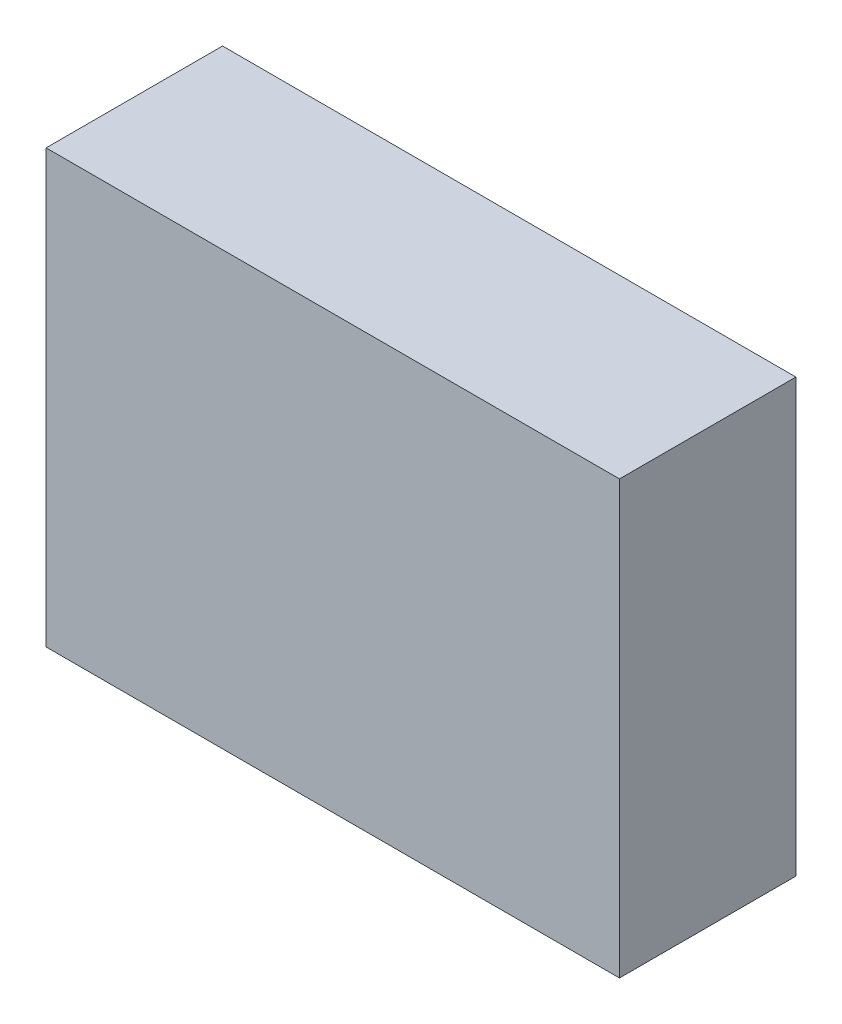
SolidWorks part; units mm, degrees
ref_plane "前视基准面" through (0, 0, 0) normal (0, 0, 1) x (1, 0, 0)
ref_plane "上视基准面" through (0, 0, 0) normal (0, 1, 0) x (1, 0, 0)
ref_plane "右视基准面" through (0, 0, 0) normal (1, 0, 0) x (0, 0, -1)
other "Configuration Table"
sketch "草图1" plane through (0, 0, 0) normal (0, 0, 1) x (1, 0, 0)
  line L1 (-25, -20) -> (40, -20)
  line L2 (-25, -20) -> (-25, 29)
  line L3 (-25, 29) -> (40, 29)
  line L4 (40, -20) -> (40, 29)
extrude "凸台-拉伸1" add sketch "草图1" along normal blind 20
